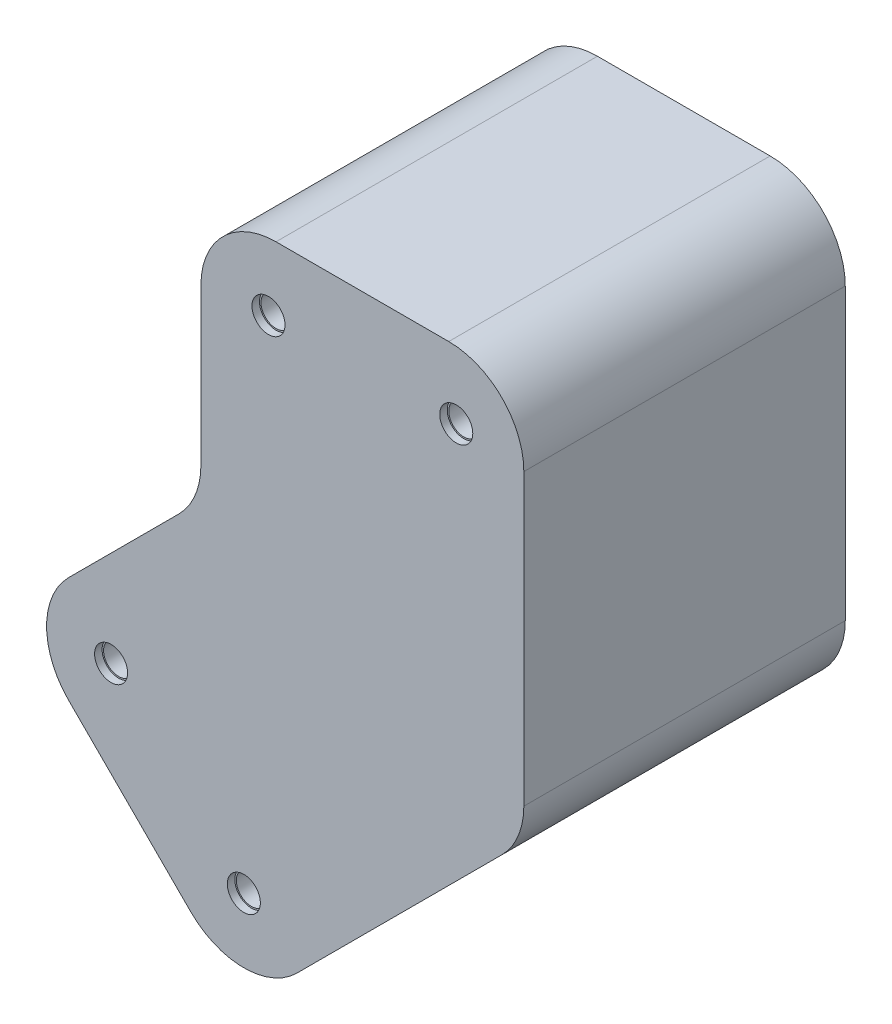
SolidWorks part; units mm, degrees
ref_plane "Front Plane" through (0, 0, 0) normal (0, 0, 1) x (1, 0, 0)
ref_plane "Top Plane" through (0, 0, 0) normal (0, 1, 0) x (1, 0, 0)
ref_plane "Right Plane" through (0, 0, 0) normal (1, 0, 0) x (0, 0, -1)
sketch "Sketch1" plane through (0, 0, 0) normal (0, 0, 1) x (1, 0, 0)
  line L0 (61.4949, 108.8173) -> (61.4949, 79.1726) construction
  line L1 (61.4949, 79.1726) -> (40.533, 58.2107) construction
  line L2 (40.533, 58.2107) -> (58.2107, 40.533) construction
  line L3 (58.2107, 40.533) -> (86.4949, 68.8173) construction
  line L4 (86.4949, 68.8173) -> (86.4949, 108.8173) construction
  line L5 (86.4949, 108.8173) -> (61.4949, 108.8173) construction
  line L8 (51.0054, 83.5175) -> (95.4621, 65.103) construction
  line L10 (40.533, 58.2107) -> (33.8155, 64.9282) construction
  line L11 (58.2107, 40.533) -> (64.9282, 33.8155) construction
  dimension "D1" = 40
  dimension "D2" = 25
sketch "Sketch3" plane through (0, 0, 0) normal (0, 0, 1) x (1, 0, 0)
  line L27 (52.4949, 117.8173) -> (52.4949, 82.9005)
  line L28 (95.4949, 117.8173) -> (52.4949, 117.8173)
  line L29 (95.4949, 65.0894) -> (95.4949, 117.8173)
  line L30 (58.2107, 27.8051) -> (95.4949, 65.0894)
  line L31 (27.8051, 58.2107) -> (58.2107, 27.8051)
  line L32 (52.4949, 82.9005) -> (27.8051, 58.2107)
  line L33 (52.4949, 117.8173) -> (52.4949, 82.9005)
  line L34 (95.4949, 117.8173) -> (52.4949, 117.8173)
  line L35 (95.4949, 65.0894) -> (95.4949, 117.8173)
  line L36 (58.2107, 27.8051) -> (95.4949, 65.0894)
  line L37 (27.8051, 58.2107) -> (58.2107, 27.8051)
  line L38 (52.4949, 82.9005) -> (27.8051, 58.2107)
  dimension "D1" = 9
extrude "Boss-Extrude1" add sketch "Sketch3" along normal blind 42.8
hole_wizard "CBORE for M5 Hex Head Cap Screw1" positions "Sketch6" profile "Sketch5" counterbore size "M5" standard "ANSI Metric"
sketch "Sketch6" plane through (0, 0, 0) normal (0, 0, -1) x (-1, 0, 0)
  point P0 (-86.4949, 108.8173)
  point P3 (-61.4949, 108.8173)
  point P6 (-58.2107, 40.533)
  point P9 (-40.533, 58.2107)
sketch "Sketch5" plane through (86.4949, 108.8173, 0) normal (1, 0, 0) x (0, 1, 0)
  line L0 (0, 0) -> (0, 6.7017)
  line L1 (0, 6.7017) -> (2, 5.5)
  line L2 (2, 5.5) -> (2, 1)
  line L3 (2, 1) -> (2.2, 1)
  line L4 (2.2, 1) -> (2.2, 0)
  line L5 (2.2, 0) -> (0, 0)
  line L10 (0, 6.7017) -> (-2, 5.5) construction
  line L11 (0, -6.35) -> (0, 107.95) construction
  dimension "Hole Dia." = 4
  dimension "Hole Depth" = 5.5
  dimension "C'Bore Dia." = 4.4
  dimension "C'Bore Depth" = 1
  dimension "Drill Angle" = 118
hole_wizard "CBORE for M5 Hex Head Cap Screw2" positions "Sketch7" profile "Sketch8" counterbore size "M5" standard "ANSI Metric"
sketch "Sketch7" plane through (0, 0, 42.8) normal (0, 0, 1) x (1, 0, 0)
  point P0 (61.4949, 108.8173)
  point P3 (86.4949, 108.8173)
  point P6 (58.2107, 40.533)
  point P9 (40.533, 58.2107)
sketch "Sketch8" plane through (61.4949, 108.8173, 42.8) normal (1, 0, 0) x (0, -1, 0)
  line L0 (0, 0) -> (0, 6.7017)
  line L1 (0, 6.7017) -> (2, 5.5)
  line L2 (2, 5.5) -> (2, 1)
  line L3 (2, 1) -> (2.2, 1)
  line L4 (2.2, 1) -> (2.2, 0)
  line L5 (2.2, 0) -> (0, 0)
  line L10 (0, 6.7017) -> (-2, 5.5) construction
  line L11 (0, -6.35) -> (0, 107.95) construction
  dimension "Hole Dia." = 4
  dimension "Hole Depth" = 5.5
  dimension "C'Bore Dia." = 4.4
  dimension "C'Bore Depth" = 1
  dimension "Drill Angle" = 118
fillet "Fillet1" radius 10 6 edges at (58.2107, 27.8051, 21.4) (95.4949, 65.0894, 21.4) (95.4949, 117.8173, 21.4) (52.4949, 117.8173, 21.4) (52.4949, 82.9005, 21.4) (27.8051, 58.2107, 21.4)
